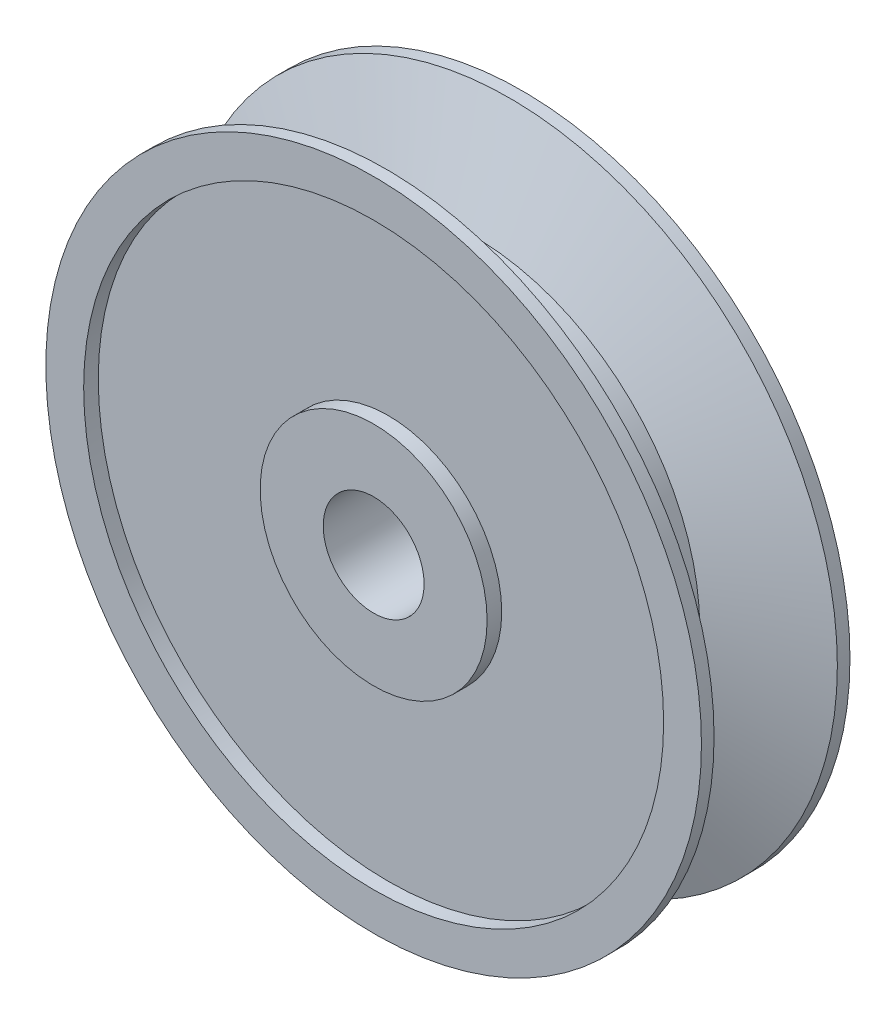
SolidWorks part; units mm, degrees
ref_plane "Front Plane" through (0, 0, 0) normal (0, 0, 1) x (1, 0, 0)
ref_plane "Top Plane" through (0, 0, 0) normal (0, 1, 0) x (1, 0, 0)
ref_plane "Right Plane" through (0, 0, 0) normal (1, 0, 0) x (0, 0, -1)
sketch "Sketch1" plane through (0, 0, 0) normal (0, 0, 1) x (1, 0, 0)
  line L0 (0, 0) -> (27.1229, 0) construction
  line L2 (0, 4) -> (5.89, 4)
  line L3 (5.89, 4) -> (5.89, 9)
  line L4 (5.89, 9) -> (4.7309, 9)
  line L5 (4.7309, 9) -> (4.7309, 23)
  line L6 (4.7309, 23) -> (5.89, 23)
  line L7 (5.89, 23) -> (5.89, 26)
  line L8 (5.89, 26) -> (0, 26)
  line L9 (0, 26) -> (0, 4)
  dimension "D1" = 4
  dimension "D2" = 5.89
  dimension "D3" = 22
  dimension "D4" = 3
  dimension "D5" = 5
  dimension "D6" = 5.89
revolve "Revolve1" add sketch "Sketch1" angle 360 about L0
sketch "Sketch2" plane through (0, 0, 0) normal (0, 0, 1) x (1, 0, 0)
  line L0 (0, 0) -> (10.1425, 0) construction
  line L2 (0, 18) -> (1.9778, 18)
  line L3 (1.9778, 18) -> (4.8896, 26)
  line L4 (5.89, 26) -> (0, 26) construction
  line L5 (4.8896, 26) -> (0, 26)
  line L6 (0, 26) -> (0, 18)
  dimension "D1" = 110
  dimension "D2" = 8
revolve "Cut-Revolve1" cut sketch "Sketch2" angle 360 about L0
mirror "Mirror1" of "Revolve1", "Cut-Revolve1"
move or copy body "Body-Move/Copy1" bodies to move or copy 103 copy no rotation origin (0, 0, 0) rotation axis (0, 1, 0) rotation angle 90
